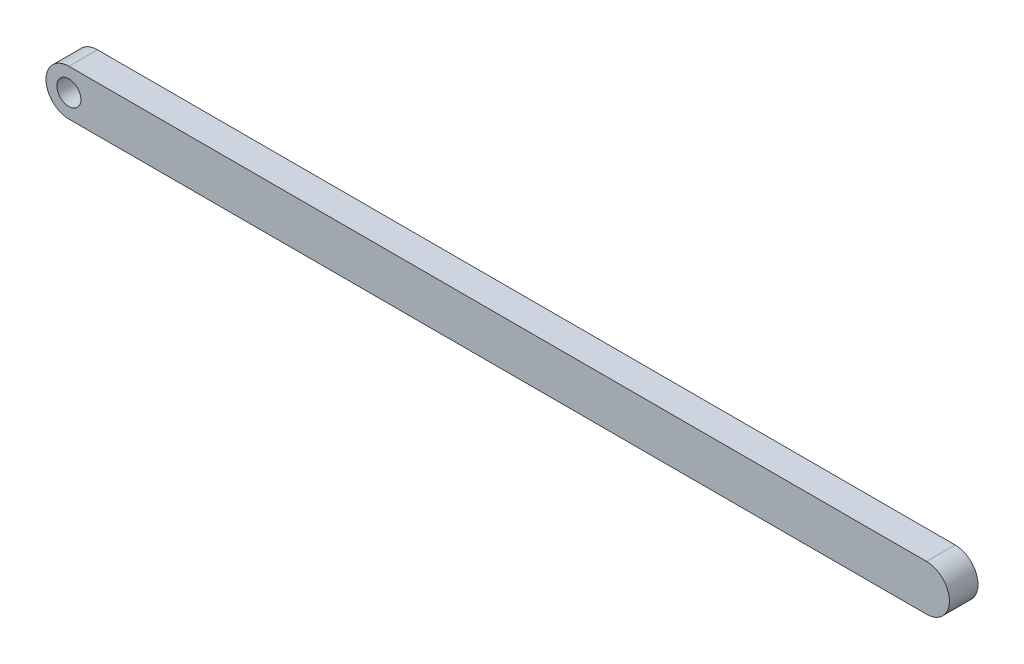
SolidWorks part; units mm, degrees
ref_plane "정면" through (0, 0, 0) normal (0, 0, 1) x (1, 0, 0)
ref_plane "윗면" through (0, 0, 0) normal (0, 1, 0) x (1, 0, 0)
ref_plane "우측면" through (0, 0, 0) normal (1, 0, 0) x (0, 0, -1)
sketch "스케치1" plane through (0, 0, 0) normal (0, 0, 1) x (1, 0, 0)
  line L0 (0, 0) -> (150, 0) construction
  line L1 (0, 4) -> (150, 4)
  line L2 (0, -4) -> (150, -4)
  circle A0 centre (0, 0) radius 2.1
  arc A1 (0, 4) -> (0, -4) centre (0, 0) ccw
  arc A2 (150, -4) -> (150, 4) centre (150, 0) ccw
  point P3 (75, 0)
  dimension "D1" = 4.2
  dimension "D3" = 4
  dimension "D2" = 150
extrude "보스-돌출1" add sketch "스케치1" along normal mid plane 5
